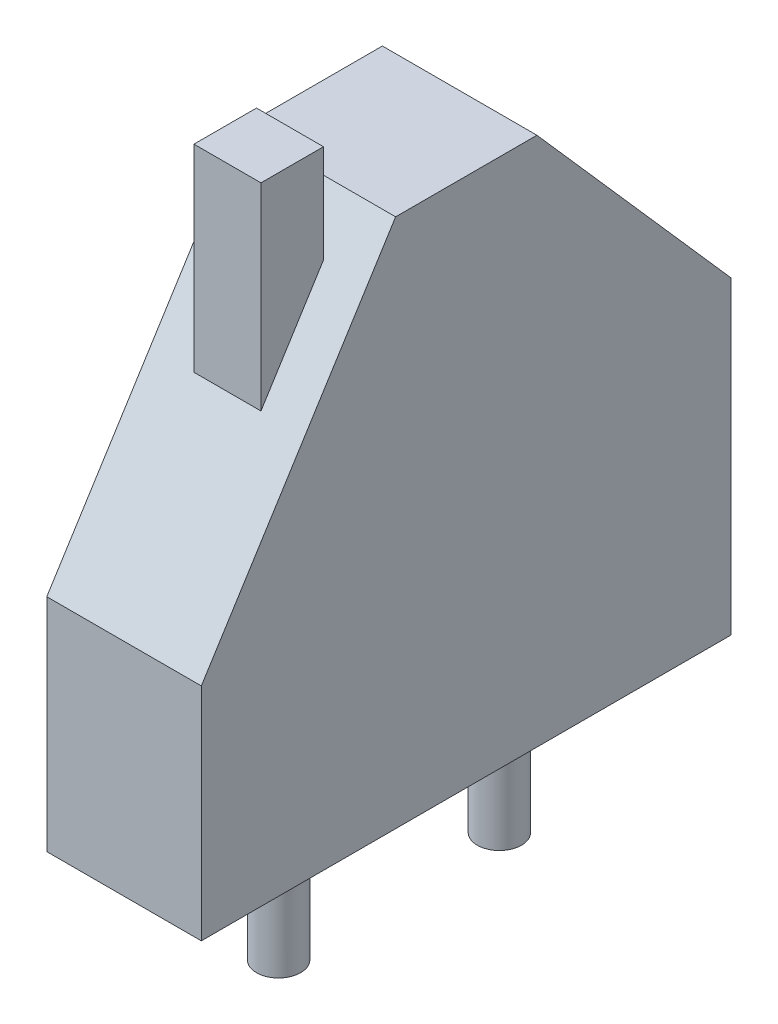
SolidWorks part; units mm, degrees
ref_plane "前视基准面" through (0, 0, 0) normal (0, 0, 1) x (1, 0, 0)
ref_plane "上视基准面" through (0, 0, 0) normal (0, 1, 0) x (1, 0, 0)
ref_plane "右视基准面" through (0, 0, 0) normal (1, 0, 0) x (0, 0, -1)
sketch "草图1" plane through (0, 0, 0) normal (0, 1, 0) x (1, 0, 0)
  line L0 (-45.7415, 0) -> (52.4503, 0) construction
  line L1 (-1.75, 6) -> (1.75, 6)
  line L2 (-1.75, 6) -> (-1.75, -6)
  line L3 (-1.75, -6) -> (1.75, -6)
  line L4 (1.75, 6) -> (1.75, -6)
  line L5 (0, 37.5081) -> (0, -35.6784) construction
  dimension "D1" = 3.5
  dimension "D2" = 12
extrude "拉伸1" add sketch "草图1" along normal blind 12
sketch "草图2" plane through (0, 0, 0) normal (0, -1, 0) x (1, 0, 0)
  line L0 (0, -7.7319) -> (0, 7.3875) construction
  line L1 (3.4268, 0) -> (-3.9951, 0) construction
  circle A0 centre (0, 2.5) radius 0.5
  circle A1 centre (0, -2.5) radius 0.5
  dimension "D2" = 1
  dimension "D3" = 1
  dimension "D1" = 2.5
  dimension "D4" = 2.5
extrude "拉伸2" add sketch "草图2" along normal blind 3
sketch "草图3" plane through (1.75, 0, 0) normal (1, 0, 0) x (0, 0, -1)
  line L0 (0, -1.7938) -> (0, 18.4087) construction
  line L1 (-1.6, 12) -> (-6, 5)
  line L2 (-6, 12) -> (6, 12) construction
  line L3 (-6, 12) -> (-6, 0) construction
  line L4 (1.6, 12) -> (6, 7)
  line L5 (6, 12) -> (6, 0) construction
  line L6 (-6, 5) -> (-6, 12)
  line L7 (-6, 12) -> (-1.6, 12)
  line L8 (6, 7) -> (6, 12)
  line L9 (6, 12) -> (1.6, 12)
  dimension "D1" = 1.6
  dimension "D2" = 7
  dimension "D3" = 1.6
  dimension "D4" = 5
extrude "切除-拉伸1" cut sketch "草图3" against normal blind 5
sketch "草图4" plane through (0, 0, 0) normal (0, -1, 0) x (1, 0, 0)
  line L0 (0, -1.0391) -> (0, 5.0529) construction
  line L1 (-0.7586, 3.6582) -> (0.7586, 3.6582)
  line L2 (-0.7586, 3.6582) -> (-0.7586, 2.2421)
  line L3 (-0.7586, 2.2421) -> (0.7586, 2.2421)
  line L4 (0.7586, 3.6582) -> (0.7586, 2.2421)
extrude "凸台-拉伸1" add sketch "草图4" against normal blind 13.2
